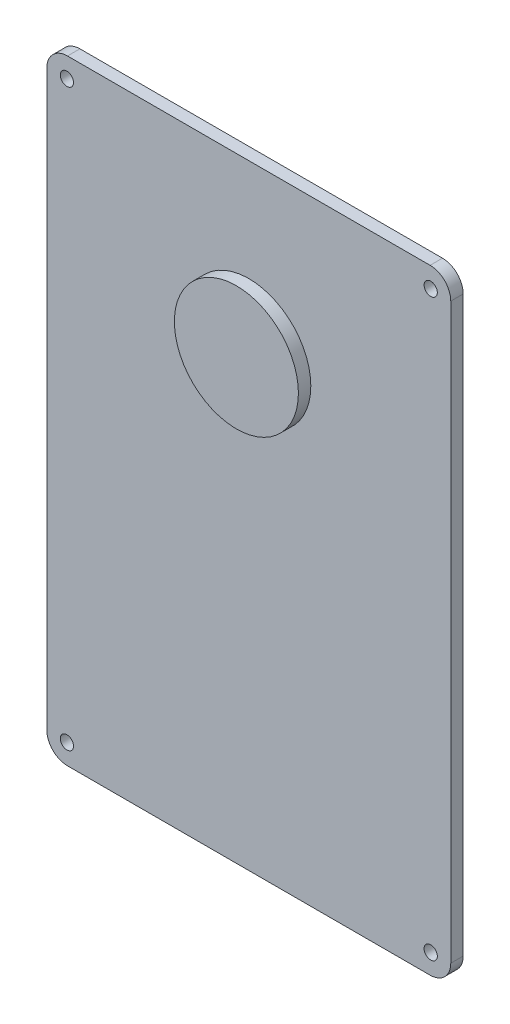
SolidWorks part; units mm, degrees
ref_plane "前视基准面" through (0, 0, 0) normal (0, 0, 1) x (1, 0, 0)
ref_plane "上视基准面" through (0, 0, 0) normal (0, 1, 0) x (1, 0, 0)
ref_plane "右视基准面" through (0, 0, 0) normal (1, 0, 0) x (0, 0, -1)
sketch "草图1" plane through (0, 0, 0) normal (0, 0, 1) x (1, 0, 0)
  line L1 (48.85, -74.35) -> (-48.85, -74.35)
  line L2 (48.85, -74.35) -> (48.85, 74.35)
  line L3 (48.85, 74.35) -> (-48.85, 74.35)
  line L4 (-48.85, -74.35) -> (-48.85, 74.35)
  line L5 (48.85, -74.35) -> (-48.85, 74.35) construction
  line L6 (48.85, 74.35) -> (-48.85, -74.35) construction
  point P0 (0, 0)
  dimension "D1" = 97.7
  dimension "D2" = 148.7
extrude "凸台-拉伸1" add sketch "草图1" along normal blind 3
fillet "圆角1" radius 5 4 edges at (-48.85, -74.35, 1.5) (48.85, -74.35, 1.5) (48.85, 74.35, 1.5) (-48.85, 74.35, 1.5)
sketch "草图2" plane through (0, 0, 3) normal (0, 0, 1) x (1, 0, 0)
  line L0 (0, 69.5) -> (0, -69.5) construction
  line L1 (-44, 69.5) -> (44, 69.5) construction
  line L2 (-44, 69.5) -> (-44, -69.5) construction
  line L3 (-44, -69.5) -> (44, -69.5) construction
  line L4 (44, 69.5) -> (44, -69.5) construction
  line L5 (-44, 69.5) -> (44, -69.5) construction
  line L6 (-44, -69.5) -> (44, 69.5) construction
  circle A0 centre (-44, 69.5) radius 1.6
  circle A1 centre (44, 69.5) radius 1.6
  circle A2 centre (-44, -69.5) radius 1.6
  circle A3 centre (44, -69.5) radius 1.6
  point P0 (0, 0)
  dimension "D3" = 3.2
  dimension "D4" = 3.2
  dimension "D5" = 3.2
  dimension "D6" = 3.2
  dimension "D1" = 139
  dimension "D2" = 88
extrude "切除-拉伸1" cut sketch "草图2" against normal up to next
sketch "草图3" plane through (0, 0, 3) normal (0, 0, 1) x (1, 0, 0)
  line L0 (0, 74.35) -> (0, -74.35) construction
  line L1 (43.85, 74.35) -> (-43.85, 74.35) construction
  line L2 (-43.85, -74.35) -> (43.85, -74.35) construction
  circle A0 centre (0, 34.65) radius 15
  dimension "D2" = 30
  dimension "D1" = 109
extrude "凸台-拉伸2" add sketch "草图3" along normal blind 3
sketch "草图4" plane through (0, 0, 0) normal (0, 0, -1) x (-1, 0, 0)
  line L0 (0, 74.35) -> (0, -74.35) construction
  line L1 (-43.85, 74.35) -> (43.85, 74.35) construction
  line L2 (43.85, -74.35) -> (-43.85, -74.35) construction
  line L3 (-12.5, 34.65) -> (12.5, 34.65)
  arc A0 (-12.5, 34.65) -> (12.5, 34.65) centre (0, 34.65) ccw
  dimension "D2" = 25
  dimension "D1" = 109
extrude "切除-拉伸2" cut sketch "草图4" against normal blind 4.5
sketch "草图5" plane through (0, 0, 4.5) normal (0, 0, -1) x (-1, 0, 0)
  line L0 (12.5, 34.65) -> (-12.5, 34.65) construction
  circle A0 centre (0, 34.65) radius 12.5
extrude "切除-拉伸3" cut sketch "草图5" along normal blind 3
sketch "草图6" plane through (0, 0, 0) normal (0, 0, -1) x (-1, 0, 0)
  line L0 (-38.85, 55.95) -> (-38.85, -64.35)
  line L1 (-38.85, -64.35) -> (-28.65, -64.35)
  line L2 (-28.65, -64.35) -> (-28.65, 55.95)
  line L3 (-28.65, 55.95) -> (-38.85, 55.95)
  line L4 (43.85, -74.35) -> (-43.85, -74.35) construction
  line L5 (-48.85, -69.35) -> (-48.85, 69.35) construction
  line L6 (28.65, 55.9) -> (32.1181, -64.35)
  line L7 (32.1181, -64.35) -> (38.85, -64.35)
  line L8 (38.85, -64.35) -> (38.85, 55.9)
  line L9 (38.85, 55.9) -> (28.65, 55.9)
  line L10 (48.85, 69.35) -> (48.85, -69.35) construction
  line L11 (-15.05, 66.05) -> (-15.05, 55.95)
  line L12 (-15.05, 55.95) -> (15.05, 55.95)
  line L13 (15.05, 55.95) -> (15.05, 66.05)
  line L14 (15.05, 66.05) -> (-15.05, 66.05)
  line L15 (-15.05, -54.25) -> (-15.05, -64.35)
  line L16 (-15.05, -64.35) -> (15.05, -64.35)
  line L17 (15.05, -64.35) -> (15.05, -54.25)
  line L18 (15.05, -54.25) -> (-15.05, -54.25)
  line L19 (-43.85, 74.35) -> (43.85, 74.35) construction
  point P20 (0, 66.05)
  point P23 (0, -54.25)
  point P24 (0, 74.35)
  dimension "D1" = 10.2
  dimension "D2" = 120.3
  dimension "D3" = 10
  dimension "D4" = 10
  dimension "D5" = 10.2
  dimension "D6" = 120.3
  dimension "D7" = 10
  dimension "D8" = 10
  dimension "D9" = 30.1
  dimension "D10" = 10.1
  dimension "D11" = 10.1
  dimension "D12" = 30.1
extrude "切除-拉伸4" cut sketch "草图6" against normal blind 2.1
